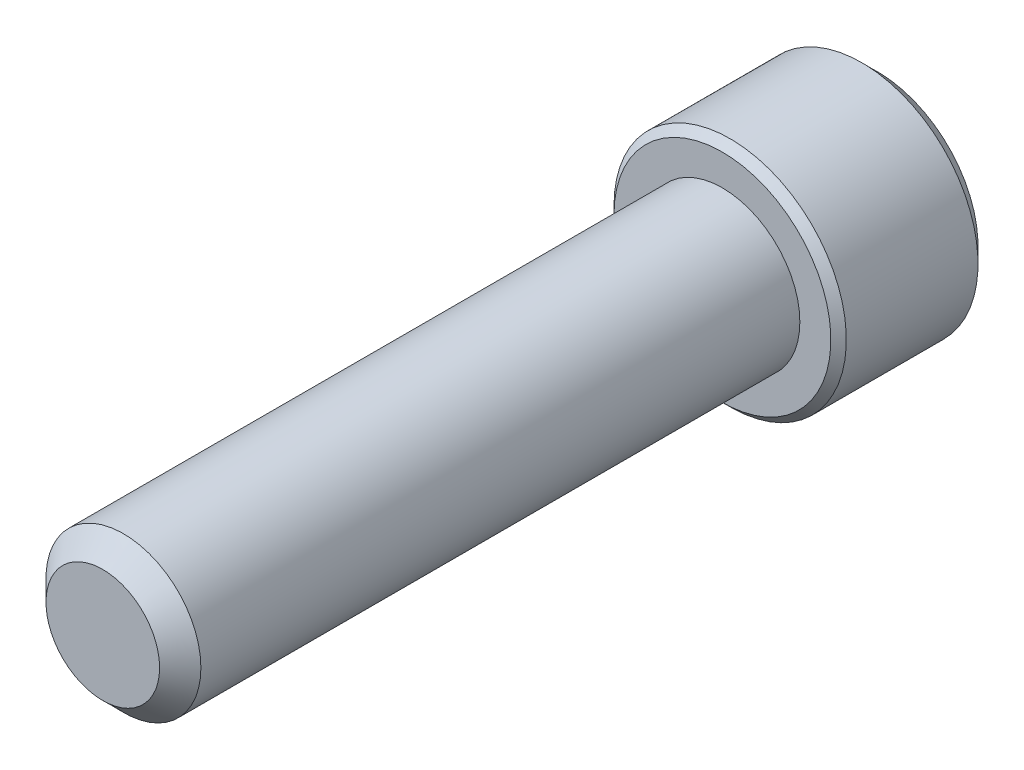
SolidWorks part; units mm, degrees
ref_plane "Front Plane" through (0, 0, 0) normal (0, 0, 1) x (1, 0, 0)
ref_plane "Top Plane" through (0, 0, 0) normal (0, 1, 0) x (1, 0, 0)
ref_plane "Right Plane" through (0, 0, 0) normal (1, 0, 0) x (0, 0, -1)
sketch "Sketch1" plane through (0, 0, 0) normal (0, 0, 1) x (1, 0, 0)
  line L0 (0, 3.9688) -> (0, -3.9688) construction
  circle A0 centre (0, 0) radius 3.9688
  dimension "OD" = 7.9375
extrude "Extrude1" add sketch "Sketch1" against normal blind 31.75
sketch "Sketch6" plane through (0, 0, -31.75) normal (0, 0, -1) x (-1, 0, 0)
  circle A0 centre (0, 0) radius 5.9531
  dimension "head dia" = 11.9062
extrude "Extrude2" add sketch "Sketch6" along normal blind 7.9375
sketch "Sketch7" plane through (0, 0, -39.6875) normal (0, 0, -1) x (-1, 0, 0)
  line L1 (0, 3.6662) -> (-3.175, 1.8331)
  line L2 (-3.175, 1.8331) -> (-3.175, -1.8331)
  line L3 (-3.175, -1.8331) -> (0, -3.6662)
  line L4 (0, -3.6662) -> (3.175, -1.8331)
  line L5 (3.175, -1.8331) -> (3.175, 1.8331)
  line L6 (3.175, 1.8331) -> (0, 3.6662)
  circle A0 centre (0, 0) radius 3.175 construction
  dimension "hex dia" = 6.35
extrude "Cut-Extrude1" cut sketch "Sketch7" against normal blind 4.7625
sketch "Sketch8" plane through (0, 0, -39.6875) normal (0, 0, -1) x (-1, 0, 0)
  circle A0 centre (0, 0) radius 3.6662
extrude "Cut-Extrude2" cut sketch "Sketch8" against normal blind 0.7937 draft 45
chamfer "Chamfer1" distance 0.7937 angle 45 1 edges at (-5.9531, 0, -39.6875)
chamfer "Chamfer2" distance 0.3969 angle 45 1 edges at (-5.9531, 0, -31.75)
chamfer "Chamfer3" distance 1.0583 angle 45 1 edges at (3.9688, 0, 0)
